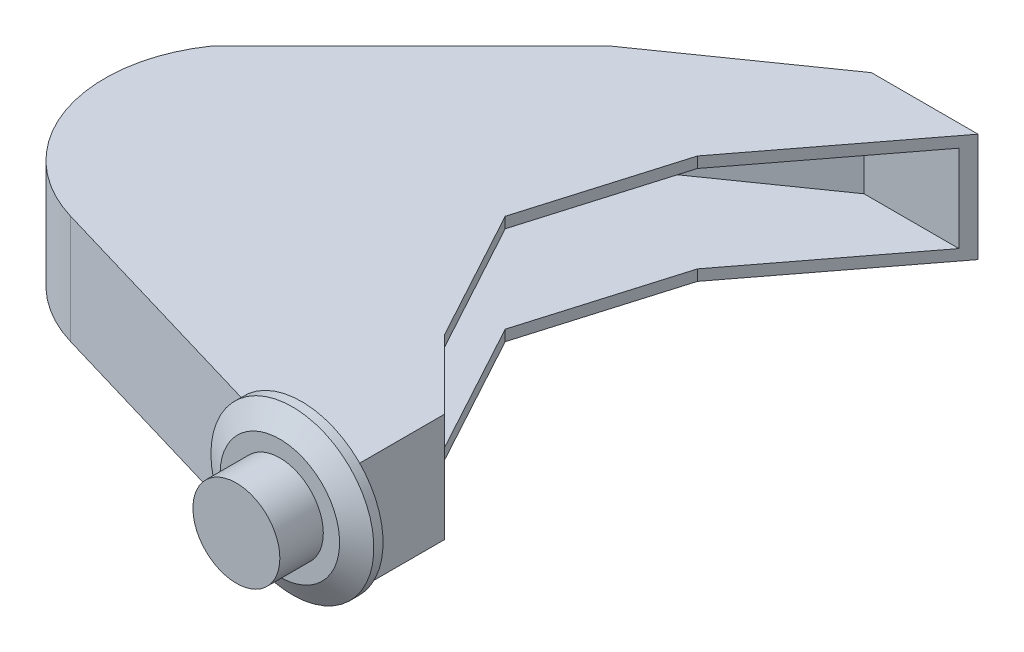
SolidWorks part; units mm, degrees
material "Mahogany"
ref_plane "Front Plane" through (0, 0, 0) normal (0, 0, 1) x (1, 0, 0)
ref_plane "Top Plane" through (0, 0, 0) normal (0, 1, 0) x (1, 0, 0)
ref_plane "Right Plane" through (0, 0, 0) normal (1, 0, 0) x (0, 0, -1)
sketch "Sketch1" plane through (0, 0, 0) normal (0, 0, 1) x (1, 0, 0)
  circle A0 centre (0, 0) radius 4
  dimension "D1" = 8
extrude "Boss-Extrude1" add sketch "Sketch1" against normal blind 4
sketch "Sketch2" plane through (0, 0, -4) normal (0, 0, -1) x (-1, 0, 0)
  circle A0 centre (0, 0) radius 7.5
  dimension "D1" = 15
extrude "Boss-Extrude2" add sketch "Sketch2" along normal blind 2
chamfer "Chamfer1" distance 2 angle 30 1 edges at (-7.5, 0, -4)
sketch "Sketch3" plane through (0, 0, 0) normal (0, 1, 0) x (1, 0, 0)
  line L13 (5.0932, 6) -> (-5.4651, 6)
  line L14 (7.5, 6) -> (-7.5, 6) construction
  line L32 (-5.4651, 6) -> (-27.9288, 12.6472)
  line L33 (-35.0041, 32.6318) -> (-16.5563, 51.0796)
  line L34 (-16.5563, 51.0796) -> (-2.4826, 60.933)
  line L35 (-2.4826, 60.933) -> (7.3235, 60.933)
  line L36 (7.3235, 60.933) -> (-3.848, 46.2859)
  line L37 (-3.848, 46.2859) -> (-7.8883, 32.6318)
  line L38 (-7.8883, 32.6318) -> (-1.2176, 20.354)
  line L39 (-1.2176, 20.354) -> (5.0932, 14.0432)
  line L40 (5.0932, 14.0432) -> (5.0932, 6)
  arc A2 (-27.9288, 12.6472) -> (-35.0041, 32.6318) centre (-24.212, 25.2079) cw
extrude "Boss-Extrude3" add sketch "Sketch3" along normal mid plane 10 separate body
shell "Shell3" thickness 1
